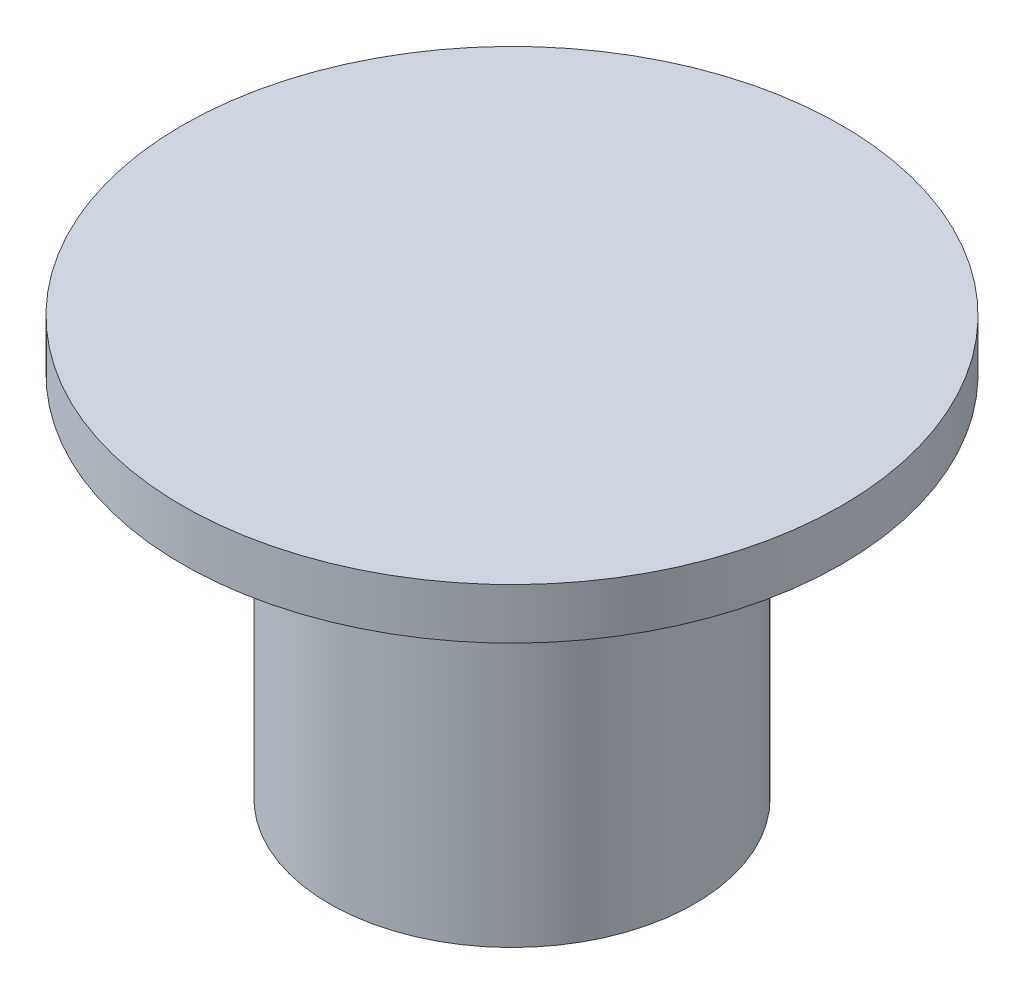
SolidWorks part; units mm, degrees
ref_plane "前视基准面" through (0, 0, 0) normal (0, 0, 1) x (1, 0, 0)
ref_plane "上视基准面" through (0, 0, 0) normal (0, 1, 0) x (1, 0, 0)
ref_plane "右视基准面" through (0, 0, 0) normal (1, 0, 0) x (0, 0, -1)
sketch "草图1" plane through (0, 0, 0) normal (0, 0, 1) x (1, 0, 0)
  line L0 (0, 0) -> (0, 2)
  line L2 (1.5, 2) -> (1.5, 0)
  line L3 (1.5, 0) -> (11, 0)
  line L6 (13, 16) -> (9.2, 16)
  line L7 (9.2, 1.5) -> (9.2, 4)
  line L8 (9.2, 4) -> (11, 4)
  line L9 (11, 4) -> (11, 5.5)
  line L10 (11, 5.5) -> (9.2, 5.5)
  line L11 (9.2, 5.5) -> (9.2, 8)
  line L12 (9.2, 8) -> (11, 8)
  line L13 (11, 8) -> (11, 9.5)
  line L14 (11, 9.5) -> (9.2, 9.5)
  line L15 (9.2, 9.5) -> (9.2, 12)
  line L16 (11, 0) -> (11, 1.5)
  line L17 (9.2, 12) -> (11, 12)
  line L18 (9.2, 1.5) -> (11, 1.5)
  line L19 (11, 12) -> (11, 13.5)
  line L20 (11, 13.5) -> (9.2, 13.5)
  line L21 (9.2, 13.5) -> (9.2, 16)
  line L22 (0, 0) -> (0, -1.5846)
  line L23 (0, -1.5846) -> (13, -1.5846)
  line L25 (13, 16) -> (13, -1.5846)
  line L26 (0, 2) -> (1.5, 2)
  line L27 (7.2, 1.5) -> (7.2, 16)
  line L28 (7.2, 16) -> (13, 16)
  line L29 (13, 18) -> (0, 18)
  line L30 (0, 18) -> (0, 2)
  line L31 (1.5, 2) -> (1.5, 1.5)
  line L32 (0, 2) -> (1.6, 2)
  line L33 (13, 16) -> (13, 18)
  line L34 (1.6, 2) -> (1.6, 1.5)
  line L35 (1.6, 1.5) -> (7.2, 1.5)
  dimension "D1" = 2.5
  dimension "D2" = 1.5
  dimension "D3" = 2
  dimension "D4" = 11
  dimension "D5" = 1.5
  dimension "D6" = 2.5
  dimension "D7" = 1.5
  dimension "D8" = 2.5
  dimension "D9" = 1.5
  dimension "D10" = 1.5
  dimension "D11" = 2.5
  dimension "D12" = 13
  dimension "D13" = 2
  dimension "D14" = 5.7
  dimension "D15" = 1.8
  dimension "D16" = 1.8
  dimension "D17" = 1.8
  dimension "D18" = 1.8
  dimension "D19" = 1.8
  dimension "D20" = 1.8
  dimension "D21" = 1.8
  dimension "D22" = 3.8
  dimension "D23" = 0.5
  dimension "D24" = 1.6
revolve "旋转2" add sketch "草图1" angle 360 about L30
